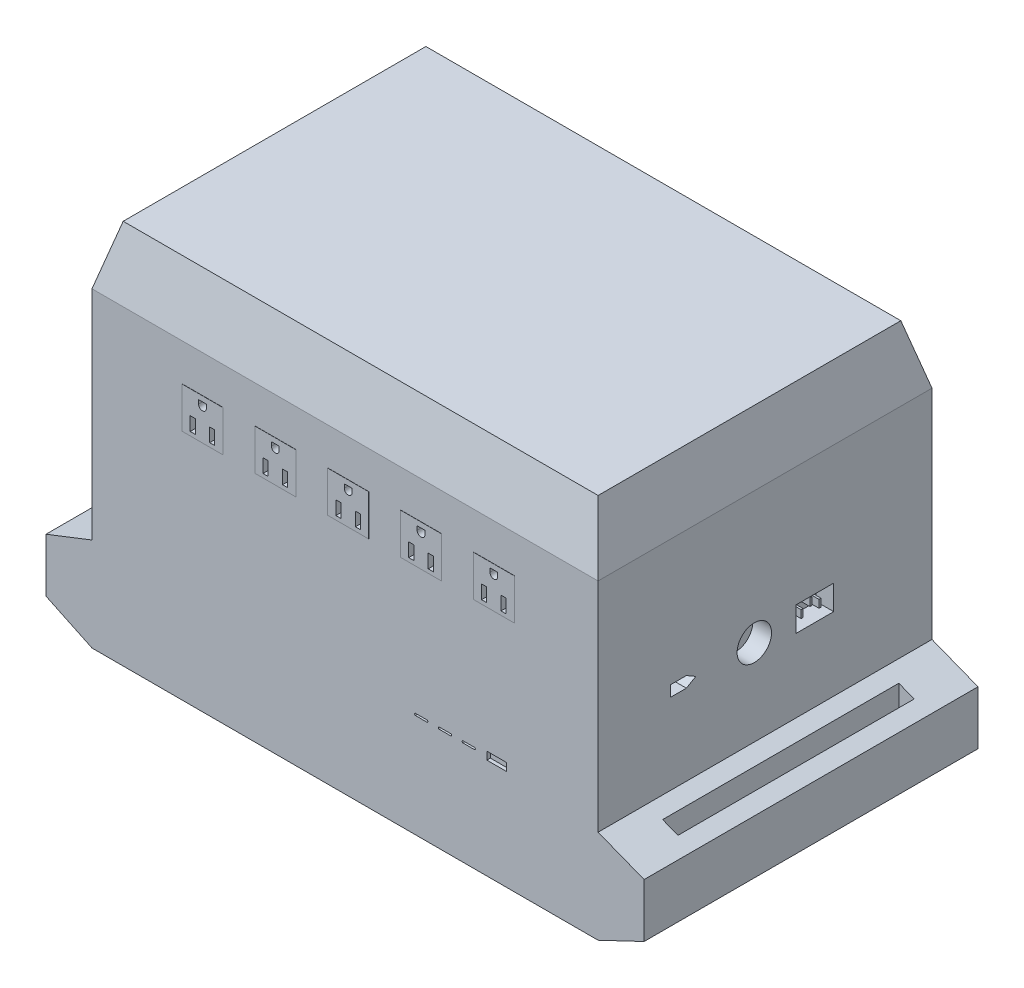
SolidWorks part; units mm, degrees
ref_plane "Front Plane" through (0, 0, 0) normal (0, 0, 1) x (1, 0, 0)
ref_plane "Top Plane" through (0, 0, 0) normal (0, 1, 0) x (1, 0, 0)
ref_plane "Right Plane" through (0, 0, 0) normal (1, 0, 0) x (0, 0, -1)
ref_plane "Plane17" through (153.035, 0, 0) normal (1, 0, 0) x (0, 0, -1)
sketch "Sketch222" plane through (153.035, 0, 0) normal (1, 0, 0) x (0, 0, -1)
  line L0 (0.0344, -137.6162) -> (-0.4201, -134.1674)
  line L1 (-0.4201, -134.1674) -> (-0.7623, -134.2123)
  line L2 (-0.7623, -134.2123) -> (-0.5399, -135.9027)
  line L3 (-0.5399, -135.9027) -> (-1.9253, -136.085)
  line L4 (-1.9253, -136.085) -> (-1.8804, -136.425)
  line L5 (-1.8804, -136.425) -> (-0.495, -136.2427)
  line L6 (-0.495, -136.2427) -> (-0.3527, -137.321)
  line L7 (-0.3527, -137.321) -> (-1.7381, -137.5033)
  line L8 (-1.7381, -137.5033) -> (-1.6932, -137.8434)
  line L9 (-1.6932, -137.8434) -> (0.0344, -137.6162)
extrude "Boss-Extrude62" add sketch "Sketch222" against normal blind 0.254 separate body
sketch "Sketch227" plane through (153.035, 0, 0) normal (1, 0, 0) x (0, 0, -1)
  line L0 (-2.6961, -138.3056) -> (-4.132, -136.7877)
  line L1 (-5.7965, -138.3617) -> (-4.3606, -139.8796)
  line L2 (-4.3606, -139.8796) -> (-4.1089, -139.6412)
  line L3 (-4.1089, -139.6412) -> (-5.5448, -138.1233)
  line L4 (-4.383, -137.0246) -> (-2.9471, -138.5426)
  line L5 (-2.9471, -138.5426) -> (-2.6961, -138.3056)
  arc A0 (-4.383, -137.0246) -> (-4.7111, -136.6979) centre (-7.9745, -140.3034) ccw
  ellipse E0 centre (-5.3112, -137.3021) end of major axis (-6.0324, -138.2441) minor radius 1.0176 (-4.6789, -136.3004) -> (-5.9914, -136.5388) ccw
  ellipse E1 centre (10.0574, -138.6279) end of major axis (26.4523, -140.0183) minor radius 3.9078 (-5.9914, -136.5388) -> (-5.7965, -138.3617) ccw
  ellipse E2 centre (-4.8312, -137.3712) end of major axis (-5.9904, -137.2348) minor radius 0.9225 (-5.7523, -136.7652) -> (-5.8918, -137.7061) ccw
  ellipse E3 centre (-5.3885, -137.8002) end of major axis (-4.9328, -136.5596) minor radius 0.909 (-4.7111, -136.6979) -> (-5.7523, -136.7652) ccw
  spline S0 degree 3 poles (-4.6789, -136.3004) (-4.6624, -136.3102) (-4.6266, -136.3315) (-4.5722, -136.3711) (-4.513, -136.4202) (-4.4466, -136.4758) (-4.376, -136.5418) (-4.2991, -136.6156) (-4.2171, -136.6987) (-4.1611, -136.7572) (-4.132, -136.7877) knots 0 0 0 0 0.078415 0.170067 0.274567 0.392386 0.523435 0.669246 0.827858 1 1 1 1
  spline S1 degree 3 poles (-5.8918, -137.7061) (-5.8855, -137.7172) (-5.8714, -137.7417) (-5.8438, -137.7795) (-5.8106, -137.8234) (-5.77, -137.8724) (-5.7243, -137.9282) (-5.6698, -137.9879) (-5.6096, -138.054) (-5.567, -138.0995) (-5.5448, -138.1233) knots 0 0 0 0 0.070557 0.155715 0.257861 0.374284 0.507047 0.65592 0.820233 1 1 1 1
extrude "Boss-Extrude63" add sketch "Sketch227" against normal blind 0.254 separate body
sketch "Sketch232" plane through (153.035, 0, 0) normal (1, 0, 0) x (0, 0, -1)
  line L0 (-5.9996, -142.3008) -> (-5.8474, -142.6247)
  line L1 (-7.6318, -140.5242) -> (-7.7447, -140.1967)
  arc A0 (-6.2751, -141.3262) -> (-6.7091, -141.6957) centre (-0.9141, -148.0627) ccw
  ellipse E0 centre (-7.9911, -141.4298) end of major axis (-8.3755, -140.6742) minor radius 0.6844 (-8.6849, -141.0759) -> (-7.969, -142.2384) ccw
  ellipse E1 centre (-5.8463, -141.6386) end of major axis (-5.9012, -141.2006) minor radius 0.4102 (-5.4506, -141.7644) -> (-5.7864, -141.2035) ccw
  ellipse E2 centre (-6.1816, -141.8844) end of major axis (-5.2666, -141.1179) minor radius 0.9529 (-5.0993, -141.8458) -> (-5.7261, -140.8481) ccw
  ellipse E3 centre (-7.0933, -141.4227) end of major axis (-7.5943, -141.8245) minor radius 0.0933 (-7.5364, -141.8226) -> (-6.8654, -141.3522) ccw
  ellipse E4 centre (-7.6202, -141.121) end of major axis (-7.0908, -140.4981) minor radius 0.6772 (-8.3455, -141.1138) -> (-7.8982, -141.8675) ccw
  spline S0 degree 3 poles (-8.6849, -141.0759) (-8.6789, -141.0504) (-8.6672, -140.9996) (-8.643, -140.9262) (-8.615, -140.8552) (-8.5813, -140.7877) (-8.5433, -140.7227) (-8.5004, -140.6608) (-8.4525, -140.6018) (-8.3997, -140.5454) (-8.3412, -140.4916) (-8.2757, -140.4414) (-8.2039, -140.3934) (-8.1249, -140.3488) (-8.0397, -140.3059) (-7.9471, -140.267) (-7.8486, -140.2296) (-7.7798, -140.2079) (-7.7447, -140.1967) knots 0 0 0 0 0.05791 0.114827 0.170369 0.226182 0.281195 0.336413 0.392147 0.448698 0.506734 0.567387 0.630606 0.69713 0.767471 0.840942 0.918622 1 1 1 1
  spline S1 degree 3 poles (-6.7091, -141.6957) (-6.7433, -141.7258) (-6.8095, -141.7842) (-6.9085, -141.8657) (-7.0037, -141.9387) (-7.095, -142.0033) (-7.1817, -142.0603) (-7.2645, -142.109) (-7.3434, -142.1492) (-7.4188, -142.182) (-7.4919, -142.2071) (-7.5629, -142.228) (-7.633, -142.2424) (-7.7023, -142.2527) (-7.7705, -142.2567) (-7.8378, -142.256) (-7.904, -142.2508) (-7.9473, -142.2425) (-7.969, -142.2384) knots 0 0 0 0 0.095916 0.185763 0.270011 0.34838 0.421264 0.488528 0.550368 0.607681 0.661372 0.71308 0.763362 0.812076 0.86039 0.907141 0.953564 1 1 1 1
  spline S2 degree 3 poles (-5.7864, -141.2035) (-5.8051, -141.2004) (-5.8422, -141.194) (-5.8989, -141.1912) (-5.9557, -141.195) (-6.0139, -141.2041) (-6.0742, -141.2212) (-6.1376, -141.2482) (-6.2061, -141.2822) (-6.2513, -141.3111) (-6.2751, -141.3262) knots 0 0 0 0 0.109431 0.217787 0.327569 0.438545 0.558024 0.68966 0.836669 1 1 1 1
  spline S3 degree 3 poles (-5.9996, -142.3008) (-5.9759, -142.2895) (-5.9302, -142.2676) (-5.865, -142.2338) (-5.805, -142.2012) (-5.7516, -142.1681) (-5.7032, -142.137) (-5.6621, -142.1048) (-5.625, -142.0754) (-5.5854, -142.0349) (-5.5424, -141.9833) (-5.5017, -141.9153) (-5.47, -141.8422) (-5.4571, -141.7906) (-5.4506, -141.7644) knots 0 0 0 0 0.098352 0.190043 0.275139 0.354175 0.425614 0.490624 0.549741 0.603019 0.702635 0.800901 0.89903 1 1 1 1
  spline S4 degree 3 poles (-5.0993, -141.8458) (-5.1091, -141.8851) (-5.1284, -141.9633) (-5.1753, -142.0749) (-5.2372, -142.1786) (-5.2996, -142.2594) (-5.3587, -142.3199) (-5.4092, -142.3657) (-5.4668, -142.41) (-5.5302, -142.4547) (-5.6006, -142.4977) (-5.6769, -142.5413) (-5.7597, -142.5841) (-5.8176, -142.6109) (-5.8474, -142.6247) knots 0 0 0 0 0.107801 0.214363 0.320668 0.42885 0.485185 0.545551 0.610286 0.678655 0.751879 0.829919 0.912587 1 1 1 1
  spline S5 degree 3 poles (-6.2863, -140.9189) (-6.2631, -140.9087) (-6.2172, -140.8887) (-6.1472, -140.8649) (-6.077, -140.8472) (-6.007, -140.8351) (-5.9366, -140.8296) (-5.8663, -140.8297) (-5.7958, -140.8349) (-5.7494, -140.8437) (-5.7261, -140.8481) knots 0 0 0 0 0.132319 0.261173 0.385741 0.509487 0.631872 0.753868 0.876254 1 1 1 1
  spline S6 degree 3 poles (-6.8654, -141.3522) (-6.8324, -141.3236) (-6.7692, -141.2689) (-6.6774, -141.1926) (-6.5936, -141.1249) (-6.5178, -141.0658) (-6.4485, -141.0169) (-6.3883, -140.9753) (-6.3353, -140.9429) (-6.3016, -140.9264) (-6.2863, -140.9189) knots 0 0 0 0 0.181047 0.345853 0.493713 0.626794 0.743261 0.844919 0.929503 1 1 1 1
  spline S7 degree 3 poles (-7.8982, -141.8675) (-7.8693, -141.872) (-7.8107, -141.881) (-7.7201, -141.8768) (-7.6275, -141.8574) (-7.5675, -141.8345) (-7.5364, -141.8226) knots 0 0 0 0 0.236659 0.47937 0.730941 1 1 1 1
  spline S8 degree 3 poles (-7.6318, -140.5242) (-7.6816, -140.5402) (-7.777, -140.5709) (-7.9096, -140.6277) (-8.0253, -140.6911) (-8.1242, -140.7614) (-8.2062, -140.839) (-8.2707, -140.924) (-8.3197, -141.0154) (-8.3369, -141.0811) (-8.3455, -141.1138) knots 0 0 0 0 0.161453 0.30907 0.444319 0.567798 0.682555 0.791157 0.895979 1 1 1 1
extrude "Boss-Extrude64" add sketch "Sketch232" against normal blind 0.254 separate body
sketch "Sketch237" plane through (153.035, 0, 0) normal (1, 0, 0) x (0, 0, -1)
  line L0 (-5.2735, -144.1601) -> (-8.4966, -145.4361)
  line L1 (-8.4966, -145.4361) -> (-7.7702, -147.2696)
  line L2 (-7.7702, -147.2696) -> (-7.4526, -147.1441)
  line L3 (-7.4526, -147.1441) -> (-8.0514, -145.6324)
  line L4 (-8.0514, -145.6324) -> (-6.7872, -145.1318)
  line L5 (-6.7872, -145.1318) -> (-6.1885, -146.6435)
  line L6 (-6.1885, -146.6435) -> (-5.873, -146.518)
  line L7 (-5.873, -146.518) -> (-6.4717, -145.0063)
  line L8 (-6.4717, -145.0063) -> (-5.4635, -144.6074)
  line L9 (-5.4635, -144.6074) -> (-4.8598, -146.1323)
  line L10 (-4.8598, -146.1323) -> (-4.5422, -146.0068)
  line L11 (-4.5422, -146.0068) -> (-5.2735, -144.1601)
extrude "Boss-Extrude65" add sketch "Sketch237" against normal blind 0.254 separate body
ref_plane "Plane18" through (0, 0, -101.854) normal (0, 0, -1) x (-1, 0, 0)
sketch "Sketch242" plane through (0, 0, -101.854) normal (0, 0, -1) x (-1, 0, 0)
  line L0 (167.1498, -19.1227) -> (-162.8502, -19.1227)
  line L1 (-162.8502, -19.1227) -> (-162.8502, -199.1227)
  line L2 (-162.8502, -199.1227) -> (-192.8502, -210.8394)
  line L3 (-192.8502, -210.8394) -> (-192.8502, -245.8394)
  line L4 (-192.8502, -245.8394) -> (-162.8502, -260.1227)
  line L5 (-162.8502, -260.1227) -> (167.1498, -260.1227)
  line L6 (167.1498, -260.1227) -> (197.1498, -245.8394)
  line L7 (197.1498, -245.8394) -> (197.1498, -210.8394)
  line L8 (197.1498, -210.8394) -> (167.1498, -199.1227)
  line L9 (167.1498, -199.1227) -> (167.1498, -19.1227)
  dimension "D1" = 241
  dimension "D2" = 330
  dimension "D3" = 180
  dimension "D4" = 35
  dimension "D5" = 390
  dimension "D6" = 32.2069
  dimension "D7" = 33.2267
  dimension "D8" = 30
  dimension "D9" = 14.2832
extrude "Boss-Extrude66" add sketch "Sketch242" against normal blind 17.62 and the other way blind 14 separate body
sketch "Sketch243" plane through (0, 0, -84.234) normal (0, 0, 1) x (1, 0, 0)
  line L0 (182.8502, -250.6005) -> (172.8502, -255.3616)
  line L1 (172.8502, -255.3616) -> (172.8502, -203.0282)
  line L2 (172.8502, -203.0282) -> (182.8502, -206.9338)
  line L3 (182.8502, -206.9338) -> (182.8502, -250.6005)
  line L4 (162.8502, -199.1227) -> (192.8502, -210.8394) construction
  line L5 (192.8502, -245.8394) -> (162.8502, -260.1227) construction
  line L6 (192.8502, -210.8394) -> (192.8502, -245.8394) construction
  line L7 (162.8502, -19.1227) -> (162.8502, -199.1227) construction
  dimension "D1" = 10
  dimension "D2" = 10
sketch "Sketch244" plane through (0, 0, -84.234) normal (0, 0, 1) x (1, 0, 0)
  line L0 (-167.1498, -260.1227) -> (-197.1498, -245.8394)
  line L1 (-197.1498, -245.8394) -> (-197.1498, -210.8394)
  line L2 (-197.1498, -210.8394) -> (-167.1498, -199.1227)
  line L3 (-167.1498, -199.1227) -> (-167.1498, -19.1227)
  line L4 (-167.1498, -19.1227) -> (162.8502, -19.1227)
  line L5 (162.8502, -19.1227) -> (162.8502, -199.1227)
  line L6 (162.8502, -199.1227) -> (192.8502, -210.8394)
  line L7 (192.8502, -210.8394) -> (192.8502, -245.8394)
  line L8 (192.8502, -245.8394) -> (162.8502, -260.1227)
  line L9 (162.8502, -260.1227) -> (-167.1498, -260.1227)
  line L10 (-167.1498, -199.1227) -> (-167.1498, -19.1227) construction
  line L11 (-167.1498, -19.1227) -> (162.8502, -19.1227) construction
  line L12 (162.8502, -19.1227) -> (162.8502, -199.1227) construction
  line L13 (192.8502, -210.8394) -> (192.8502, -245.8394) construction
  line L14 (162.8502, -199.1227) -> (192.8502, -210.8394) construction
  line L15 (192.8502, -245.8394) -> (162.8502, -260.1227) construction
  line L16 (162.8502, -260.1227) -> (-167.1498, -260.1227) construction
  line L17 (-167.1498, -260.1227) -> (-197.1498, -245.8394) construction
  line L18 (-197.1498, -245.8394) -> (-197.1498, -210.8394) construction
  line L19 (-197.1498, -210.8394) -> (-167.1498, -199.1227) construction
  line L20 (-197.1498, -245.8394) -> (-197.1498, -210.8394) construction
  line L21 (-197.1498, -210.8394) -> (-167.1498, -199.1227) construction
extrude "Boss-Extrude68" add sketch "Sketch244" along normal blind 168.468
sketch "Sketch246" plane through (0, 0, 84.234) normal (0, 0, 1) x (1, 0, 0)
  line L0 (162.8502, -199.1227) -> (192.8502, -210.8394)
  line L1 (192.8502, -210.8394) -> (192.8502, -245.8394)
  line L2 (192.8502, -245.8394) -> (162.8502, -260.1227)
  line L3 (162.8502, -260.1227) -> (-167.1498, -260.1227)
  line L4 (-167.1498, -260.1227) -> (-197.1498, -245.8394)
  line L5 (-197.1498, -245.8394) -> (-197.1498, -210.8394)
  line L6 (-197.1498, -210.8394) -> (-167.1498, -199.1227)
  line L7 (-167.1498, -199.1227) -> (-167.1498, -19.1227)
  line L8 (-167.1498, -19.1227) -> (162.8502, -19.1227)
  line L9 (162.8502, -19.1227) -> (162.8502, -199.1227)
  line L10 (162.8502, -19.1227) -> (-167.1498, -19.1227) construction
  line L11 (-167.1498, -19.1227) -> (-167.1498, -199.1227) construction
  line L12 (-197.1498, -210.8394) -> (-167.1498, -199.1227) construction
  line L13 (-197.1498, -245.8394) -> (-197.1498, -210.8394) construction
  line L14 (-167.1498, -260.1227) -> (-197.1498, -245.8394) construction
  line L15 (162.8502, -260.1227) -> (-167.1498, -260.1227) construction
  line L16 (192.8502, -245.8394) -> (162.8502, -260.1227) construction
  line L17 (192.8502, -210.8394) -> (192.8502, -245.8394) construction
  line L18 (162.8502, -199.1227) -> (192.8502, -210.8394) construction
extrude "Boss-Extrude70" add sketch "Sketch246" along normal blind 17.62
ref_plane "Plane19" through (-163.703, 0, 0) normal (-1, 0, 0) x (0, 0, 1)
sketch "Sketch252" plane through (-163.703, 0, 0) normal (-1, 0, 0) x (0, 0, 1)
  line L0 (-11.7788, -143.2) -> (-12.4793, -143.2)
  line L1 (-13.9776, -142.264) -> (-14.0224, -143.6885)
  line L2 (-14.0224, -143.6885) -> (-14.0224, -139.7)
  line L3 (-14.0224, -139.7) -> (-13.634, -139.7)
  line L4 (-13.634, -139.7) -> (-13.634, -141.3154)
  line L5 (-13.634, -141.3154) -> (-12.0929, -141.3154)
  line L6 (-12.0929, -141.3154) -> (-12.0929, -139.7)
  line L7 (-12.0929, -139.7) -> (-11.7788, -139.7)
  line L8 (-11.7788, -139.7) -> (-11.7788, -143.2)
  arc A0 (-12.4793, -143.2) -> (-13.2722, -143.1523) centre (-12.5951, -138.5088) cw
  ellipse E0 centre (-12.9672, -142.209) end of major axis (-12.0813, -141.6743) minor radius 0.9414 (-13.9776, -142.264) -> (-13.2722, -143.1523) ccw
extrude "Boss-Extrude71" add sketch "Sketch252" along normal blind 0.254
chamfer "Chamfer7" distance 10.16 angle 75.069 4 edges at (-2.1498, -19.1227, -115.854) (162.8502, -19.1227, -7) (-167.1498, -19.1227, -7) (-2.1498, -19.1227, 101.854)
sketch "Sketch253" plane through (-167.1498, 0, 0) normal (-1, 0, 0) x (0, 0, 1)
  ellipse E0 centre (-2.0861, -141.2724) end of major axis (-3.3261, -139.6136) minor radius 1.9176 (-1.9295, -143.2897) -> (-0.1122, -141.4346) ccw
  ellipse E1 centre (-2.1642, -141.6778) end of major axis (-0.9066, -142.8229) minor radius 1.5373 (-3.7917, -141.4514) -> (-1.9295, -143.2897) ccw
  ellipse E2 centre (-2.2917, -141.1164) end of major axis (-1.1535, -139.9506) minor radius 1.3696 (-1.9575, -139.6103) -> (-3.7917, -141.4514) ccw
  ellipse E3 centre (-1.5964, -141.0847) end of major axis (-0.4364, -142.2065) minor radius 1.3366 (-0.1122, -141.4346) -> (-1.9575, -139.6103) ccw
extrude "Boss-Extrude72" add sketch "Sketch253" along normal blind 0.254
sketch "Sketch254" plane through (-167.4038, 0, 0) normal (-1, 0, 0) x (0, 0, 1)
  ellipse E0 centre (-1.6109, -141.7451) end of major axis (-3.1952, -140.5735) minor radius 1.6602 (-1.9449, -139.9692) -> (-3.4776, -141.4521) ccw
  ellipse E1 centre (-1.8216, -141.3893) end of major axis (-3.4031, -141.9274) minor radius 1.5262 (-3.4776, -141.4521) -> (-1.9449, -142.9308) ccw
  ellipse E2 centre (-2.0851, -141.3466) end of major axis (-0.588, -142.1202) minor radius 1.5565 (-1.9449, -142.9308) -> (-0.4263, -141.436) ccw
  ellipse E3 centre (-1.6563, -141.149) end of major axis (-2.6855, -140.3274) minor radius 1.086 (-0.4263, -141.436) -> (-1.9449, -139.9692) ccw
extrude "Cut-Extrude49" cut sketch "Sketch254" against normal blind 0.254 from surface at -0.254 starting at face at (-167.1498, -141.4495, -1.9512)
sketch "Sketch256" plane through (-167.1498, 0, 0) normal (-1, 0, 0) x (0, 0, 1)
  line L0 (11.2404, -142.1231) -> (11.5545, -142.1231)
  line L1 (10.0632, -140.9929) -> (10.9389, -140.059)
  line L2 (10.9389, -140.059) -> (9.3109, -140.059)
  line L3 (9.3109, -140.059) -> (9.3109, -139.7)
  line L4 (9.3109, -139.7) -> (11.6891, -139.7)
  line L5 (11.6891, -139.7) -> (11.6891, -139.7318)
  ellipse E0 centre (10.5178, -142.2084) end of major axis (11.0326, -141.237) minor radius 1.0186 (10.4131, -143.2897) -> (11.5545, -142.1231) ccw
  ellipse E1 centre (10.2761, -142.3526) end of major axis (9.6685, -141.5951) minor radius 0.8865 (9.3558, -142.2493) -> (10.4131, -143.2897) ccw
  ellipse E2 centre (10.2745, -142.3612) end of major axis (9.7564, -141.9751) minor radius 0.5239 (9.6699, -142.2212) -> (10.4292, -142.9308) ccw
  ellipse E3 centre (10.1862, -141.7824) end of major axis (9.4711, -140.775) minor radius 0.9527 (10.4292, -142.9308) -> (11.2404, -142.1231) ccw
  spline S0 degree 3 poles (9.3558, -142.2493) (9.3575, -142.2005) (9.3608, -142.1039) (9.3895, -141.9619) (9.4345, -141.8244) (9.488, -141.7134) (9.5418, -141.6238) (9.5915, -141.5508) (9.6489, -141.4717) (9.7149, -141.3866) (9.7904, -141.2967) (9.8726, -141.1995) (9.9651, -141.0981) (10.0297, -141.0288) (10.0632, -140.9929) knots 0 0 0 0 0.098685 0.195638 0.292371 0.391069 0.444585 0.503948 0.57006 0.642614 0.721977 0.807955 0.900487 1 1 1 1
  spline S1 degree 3 poles (11.6891, -139.7318) (11.2366, -140.204) (10.7511, -140.7108) (10.2352, -141.2493) (10.1454, -141.346) (10.0647, -141.4357) (9.9929, -141.5187) (9.93, -141.5945) (9.8762, -141.6637) (9.8313, -141.7257) (9.7837, -141.7986) (9.7383, -141.8877) (9.6984, -141.996) (9.6742, -142.1078) (9.6713, -142.1833) (9.6699, -142.2212) knots -1.516771 -1.516771 -1.516771 -1.516771 0 0.110794 0.212813 0.306078 0.390617 0.467233 0.534451 0.593867 0.644833 0.736221 0.825037 0.911992 1 1 1 1
extrude "Boss-Extrude73" add sketch "Sketch256" along normal blind 0.254
sketch "Sketch257" plane through (-167.1498, 0, 0) normal (-1, 0, 0) x (0, 0, 1)
  line L0 (-4.2853, -143.2) -> (-4.6092, -143.2)
  line L1 (-4.6092, -143.2) -> (-5.2949, -140.6311)
  line L2 (-5.2949, -140.6311) -> (-6.3358, -143.2578)
  line L3 (-6.3358, -143.2578) -> (-7.359, -140.6507)
  line L4 (-7.359, -140.6507) -> (-8.0475, -143.2)
  line L5 (-8.0475, -143.2) -> (-8.3686, -143.2)
  line L6 (-8.3686, -143.2) -> (-8.3686, -139.7)
  line L7 (-8.3686, -139.7) -> (-7.38, -139.7)
  line L8 (-7.38, -139.7) -> (-6.3269, -142.3755)
  line L9 (-6.3269, -142.3755) -> (-5.2626, -139.7)
  line L10 (-5.2626, -139.7) -> (-4.2853, -139.7)
  line L11 (-4.2853, -139.7) -> (-4.2853, -143.2)
extrude "Boss-Extrude74" add sketch "Sketch257" along normal blind 0.254
sketch "Sketch258" plane through (-167.1498, 0, 0) normal (-1, 0, 0) x (0, 0, 1)
  line L0 (-9.1763, -143.2) -> (-11.1506, -143.2)
  line L1 (-11.1506, -143.2) -> (-11.1506, -142.841)
  line L2 (-11.1506, -142.841) -> (-9.4904, -142.841)
  line L3 (-9.4904, -142.841) -> (-9.4904, -141.7641)
  line L4 (-9.4904, -141.7641) -> (-11.1506, -141.7641)
  line L5 (-11.1506, -141.7641) -> (-11.1506, -141.4051)
  line L6 (-11.1506, -141.4051) -> (-9.4904, -141.4051)
  line L7 (-9.4904, -141.4051) -> (-9.4904, -140.059)
  line L8 (-9.4904, -140.059) -> (-11.1506, -140.059)
  line L9 (-11.1506, -140.059) -> (-11.1506, -139.7)
  line L10 (-11.1506, -139.7) -> (-9.1763, -139.7)
  line L11 (-9.1763, -139.7) -> (-9.1763, -143.2)
extrude "Boss-Extrude75" add sketch "Sketch258" along normal blind 0.254
sketch "Sketch265" plane through (-163.703, 0, 0) normal (-1, 0, 0) x (0, 0, 1)
  line L0 (13.6375, -143.2) -> (12.9904, -143.2)
  line L1 (12.9904, -143.2) -> (12.9904, -139.7)
  line L2 (12.9904, -139.7) -> (13.3045, -139.7)
  line L3 (13.3045, -139.7) -> (13.3045, -142.841)
  line L4 (13.3045, -142.841) -> (13.6375, -142.841)
  line L5 (13.6375, -142.841) -> (13.6375, -143.2)
extrude "Boss-Extrude76" add sketch "Sketch265" along normal blind 0.254
sketch "Sketch272" plane through (-163.703, 0, 0) normal (-1, 0, 0) x (0, 0, 1)
  line L0 (7.6058, -143.2) -> (7.2692, -143.2)
  line L1 (7.2692, -143.2) -> (6.1033, -140.4439)
  line L2 (6.1033, -140.4439) -> (4.9366, -143.2)
  line L3 (4.9366, -143.2) -> (4.5994, -143.2)
  line L4 (4.5994, -143.2) -> (4.5994, -136.0939)
  line L5 (4.5994, -136.0939) -> (7.6058, -143.2)
extrude "Boss-Extrude77" add sketch "Sketch272" along normal blind 0.254
ref_plane "Plane20" through (0, 0, 101.854) normal (0, 0, 1) x (1, 0, 0)
sketch "Sketch279" plane through (0, 0, 101.854) normal (0, 0, 1) x (1, 0, 0)
  line L0 (90.297, -194.691) -> (102.997, -194.691)
  line L1 (102.997, -194.691) -> (102.997, -189.611)
  line L2 (102.997, -189.611) -> (90.297, -189.611)
  line L3 (90.297, -189.611) -> (90.297, -194.691)
extrude "Cut-Extrude51" cut sketch "Sketch279" against normal blind 12.7
sketch "Sketch280" plane through (0, 0, 89.154) normal (0, 0, 1) x (1, 0, 0)
  line L0 (91.313, -193.675) -> (91.313, -190.627)
  line L1 (91.313, -190.627) -> (101.981, -190.627)
  line L2 (101.981, -190.627) -> (101.981, -193.675)
  line L3 (101.981, -193.675) -> (91.313, -193.675)
extrude "Boss-Extrude78" add sketch "Sketch280" along normal blind 11.43
sketch "Sketch281" plane through (0, 0, 101.854) normal (0, 0, 1) x (1, 0, 0)
  line L0 (82.169, -191.516) -> (74.803, -191.516)
  line L1 (74.803, -192.786) -> (82.169, -192.786)
  arc A0 (74.803, -191.516) -> (74.803, -192.786) centre (74.803, -192.151) ccw
  arc A1 (82.169, -192.786) -> (82.169, -191.516) centre (82.169, -192.151) ccw
extrude "Cut-Extrude52" cut sketch "Sketch281" against normal blind 12.7
sketch "Sketch282" plane through (0, 0, 89.154) normal (0, 0, 1) x (1, 0, 0)
  line L0 (74.803, -192.024) -> (82.169, -192.024)
  line L1 (82.169, -192.278) -> (74.803, -192.278)
  arc A0 (82.169, -192.024) -> (82.169, -192.278) centre (82.169, -192.151) cw
  arc A1 (74.803, -192.278) -> (74.803, -192.024) centre (74.803, -192.151) cw
extrude "Boss-Extrude79" add sketch "Sketch282" along normal blind 11.43
sketch "Sketch290" plane through (0, 0, 101.854) normal (0, 0, 1) x (1, 0, 0)
  line L0 (59.309, -192.786) -> (66.675, -192.786)
  line L1 (66.675, -191.516) -> (59.309, -191.516)
  arc A0 (66.675, -192.786) -> (66.675, -191.516) centre (66.675, -192.151) ccw
  arc A1 (59.309, -191.516) -> (59.309, -192.786) centre (59.309, -192.151) ccw
extrude "Cut-Extrude53" cut sketch "Sketch290" against normal blind 12.7
sketch "Sketch291" plane through (0, 0, 89.154) normal (0, 0, 1) x (1, 0, 0)
  line L0 (66.675, -192.278) -> (59.309, -192.278)
  line L1 (59.309, -192.024) -> (66.675, -192.024)
  arc A0 (59.309, -192.278) -> (59.309, -192.024) centre (59.309, -192.151) cw
  arc A1 (66.675, -192.024) -> (66.675, -192.278) centre (66.675, -192.151) cw
extrude "Boss-Extrude80" add sketch "Sketch291" along normal blind 11.43
sketch "Sketch292" plane through (0, 0, 101.854) normal (0, 0, 1) x (1, 0, 0)
  line L0 (43.815, -192.786) -> (51.181, -192.786)
  line L1 (51.181, -191.516) -> (43.815, -191.516)
  arc A0 (51.181, -192.786) -> (51.181, -191.516) centre (51.181, -192.151) ccw
  arc A1 (43.815, -191.516) -> (43.815, -192.786) centre (43.815, -192.151) ccw
extrude "Cut-Extrude54" cut sketch "Sketch292" against normal blind 12.7
sketch "Sketch293" plane through (0, 0, 89.154) normal (0, 0, 1) x (1, 0, 0)
  line L0 (51.181, -192.278) -> (43.815, -192.278)
  line L1 (43.815, -192.024) -> (51.181, -192.024)
  arc A0 (43.815, -192.278) -> (43.815, -192.024) centre (43.815, -192.151) cw
  arc A1 (51.181, -192.024) -> (51.181, -192.278) centre (51.181, -192.151) cw
extrude "Boss-Extrude81" add sketch "Sketch293" along normal blind 11.43
ref_plane "Plane21" through (163.703, 0, 0) normal (1, 0, 0) x (0, 0, -1)
sketch "Sketch301" plane through (163.703, 0, 0) normal (1, 0, 0) x (0, 0, -1)
  line L0 (51.7652, -135.255) -> (27.2288, -135.255)
  line L1 (27.2288, -135.255) -> (27.2288, -151.384)
  line L2 (27.2288, -151.384) -> (51.7652, -151.384)
  line L3 (51.7652, -151.384) -> (51.7652, -135.255)
extrude "Cut-Extrude55" cut sketch "Sketch301" against normal blind 11.43 from surface at -0.8528 starting at face at (162.8502, -128.1727, -7)
sketch "Sketch302" plane through (151.4202, 0, 0) normal (1, 0, 0) x (0, 0, -1)
  line L0 (40.132, -143.3367) -> (38.862, -143.3367)
  line L1 (38.862, -143.3367) -> (38.862, -138.2567)
  line L2 (38.862, -138.2567) -> (40.132, -138.2567)
  line L3 (40.132, -138.2567) -> (40.132, -143.3367)
extrude "Boss-Extrude82" add sketch "Sketch302" along normal blind 8.89
sketch "Sketch303" plane through (151.4202, 0, 0) normal (1, 0, 0) x (0, 0, -1)
  line L0 (34.3011, -147.2296) -> (33.0311, -147.2296)
  line L1 (33.0311, -147.2296) -> (33.0311, -142.1496)
  line L2 (33.0311, -142.1496) -> (34.3011, -142.1496)
  line L3 (34.3011, -142.1496) -> (34.3011, -147.2296)
extrude "Boss-Extrude83" add sketch "Sketch303" along normal blind 8.89
sketch "Sketch304" plane through (151.4202, 0, 0) normal (1, 0, 0) x (0, 0, -1)
  line L0 (45.9629, -147.2296) -> (44.6929, -147.2296)
  line L1 (44.6929, -147.2296) -> (44.6929, -142.1496)
  line L2 (44.6929, -142.1496) -> (45.9629, -142.1496)
  line L3 (45.9629, -142.1496) -> (45.9629, -147.2296)
extrude "Boss-Extrude84" add sketch "Sketch304" along normal blind 8.89
sketch "Sketch305" plane through (162.8502, 0, 0) normal (1, 0, 0) x (0, 0, -1)
  line L0 (-44.2985, -146.558) -> (-38.1393, -143.002)
  line L1 (-38.1393, -143.002) -> (-44.2985, -139.446)
  line L2 (-44.2985, -139.446) -> (-54.61, -139.446)
  line L3 (-54.61, -139.446) -> (-54.61, -146.558)
  line L4 (-54.61, -146.558) -> (-44.2985, -146.558)
extrude "Cut-Extrude56" cut sketch "Sketch305" against normal blind 12.7 from surface at 0 starting at face at (162.8502, -128.1727, -7)
sketch "Sketch312" plane through (-163.703, 0, 0) normal (-1, 0, 0) x (0, 0, 1)
  line L0 (2.5801, -143.2) -> (1.8937, -143.2)
  line L1 (2.0157, -141.3154) -> (2.266, -141.3154)
  line L2 (2.266, -141.3154) -> (2.266, -139.7)
  line L3 (2.266, -139.7) -> (2.5801, -139.7)
  line L4 (2.5801, -139.7) -> (2.5801, -143.2)
  ellipse E0 centre (1.8791, -143.1329) end of major axis (2.6804, -143.1327) minor radius 0.0672 (1.0966, -143.1474) -> (1.8937, -143.2) ccw
  ellipse E1 centre (1.9044, -141.8509) end of major axis (3.2154, -140.8846) minor radius 1.1514 (0.4263, -142.2612) -> (1.0966, -143.1474) ccw
  ellipse E2 centre (1.9849, -142.7491) end of major axis (3.3715, -143.7998) minor radius 1.1791 (1.1246, -141.3729) -> (0.4263, -142.2612) ccw
  ellipse E3 centre (1.6823, -141.3543) end of major axis (2.2401, -141.3352) minor radius 0.0343 (2.0157, -141.3154) -> (1.1246, -141.3729) ccw
extrude "Boss-Extrude85" add sketch "Sketch312" along normal blind 0.254
sketch "Sketch321" plane through (0, 0, 101.854) normal (0, 0, 1) x (1, 0, 0)
  line L0 (-13.335, -81.534) -> (13.335, -81.534)
  line L1 (13.335, -81.534) -> (13.335, -108.204)
  line L2 (13.335, -108.204) -> (-13.335, -108.204)
  line L3 (-13.335, -108.204) -> (-13.335, -81.534)
extrude "Boss-Extrude86" add sketch "Sketch321" along normal blind 0.127
sketch "Sketch322" plane through (0, 0, 101.981) normal (0, 0, 1) x (1, 0, 0)
  line L0 (2.54, -84.963) -> (-2.54, -84.963)
  line L1 (-2.54, -84.963) -> (-2.54, -87.503)
  line L2 (2.54, -87.503) -> (2.54, -84.963)
  arc A0 (-2.54, -87.503) -> (2.54, -87.503) centre (0, -87.503) ccw
extrude "Cut-Extrude58" cut sketch "Sketch322" against normal blind 5.08
sketch "Sketch323" plane through (0, 0, 101.981) normal (0, 0, 1) x (1, 0, 0)
  line L0 (-8.001, -105.664) -> (-4.699, -105.664)
  line L1 (-4.699, -105.664) -> (-4.699, -96.774)
  line L2 (-4.699, -96.774) -> (-8.001, -96.774)
  line L3 (-8.001, -96.774) -> (-8.001, -105.664)
extrude "Cut-Extrude59" cut sketch "Sketch323" against normal blind 5.08
ref_plane "Plane22" through (0, 0, 101.981) normal (0, 0, 1) x (1, 0, 0)
sketch "Sketch332" plane through (0, 0, 101.981) normal (0, 0, 1) x (1, 0, 0)
  line L0 (4.699, -105.664) -> (8.001, -105.664)
  line L1 (8.001, -105.664) -> (8.001, -96.774)
  line L2 (8.001, -96.774) -> (4.699, -96.774)
  line L3 (4.699, -96.774) -> (4.699, -105.664)
extrude "Cut-Extrude60" cut sketch "Sketch332" against normal blind 5.08
sketch "Sketch333" plane through (0, 0, 101.854) normal (0, 0, 1) x (1, 0, 0)
  line L0 (-60.833, -81.534) -> (-34.163, -81.534)
  line L1 (-34.163, -81.534) -> (-34.163, -108.204)
  line L2 (-34.163, -108.204) -> (-60.833, -108.204)
  line L3 (-60.833, -108.204) -> (-60.833, -81.534)
extrude "Boss-Extrude87" add sketch "Sketch333" along normal blind 0.127
sketch "Sketch334" plane through (0, 0, 101.981) normal (0, 0, 1) x (1, 0, 0)
  line L0 (-55.499, -105.664) -> (-52.197, -105.664)
  line L1 (-52.197, -105.664) -> (-52.197, -96.774)
  line L2 (-52.197, -96.774) -> (-55.499, -96.774)
  line L3 (-55.499, -96.774) -> (-55.499, -105.664)
extrude "Cut-Extrude61" cut sketch "Sketch334" against normal blind 5.08
sketch "Sketch335" plane through (0, 0, 101.981) normal (0, 0, 1) x (1, 0, 0)
  line L0 (-44.958, -84.963) -> (-50.038, -84.963)
  line L1 (-50.038, -84.963) -> (-50.038, -87.503)
  line L2 (-44.958, -87.503) -> (-44.958, -84.963)
  arc A0 (-50.038, -87.503) -> (-44.958, -87.503) centre (-47.498, -87.503) ccw
extrude "Cut-Extrude62" cut sketch "Sketch335" against normal blind 5.08
sketch "Sketch336" plane through (0, 0, 101.981) normal (0, 0, 1) x (1, 0, 0)
  line L0 (-42.799, -105.664) -> (-39.497, -105.664)
  line L1 (-39.497, -105.664) -> (-39.497, -96.774)
  line L2 (-39.497, -96.774) -> (-42.799, -96.774)
  line L3 (-42.799, -96.774) -> (-42.799, -105.664)
extrude "Cut-Extrude63" cut sketch "Sketch336" against normal blind 5.08
sketch "Sketch337" plane through (0, 0, 101.854) normal (0, 0, 1) x (1, 0, 0)
  line L0 (-108.331, -81.534) -> (-81.661, -81.534)
  line L1 (-81.661, -81.534) -> (-81.661, -108.204)
  line L2 (-81.661, -108.204) -> (-108.331, -108.204)
  line L3 (-108.331, -108.204) -> (-108.331, -81.534)
extrude "Boss-Extrude88" add sketch "Sketch337" along normal blind 0.127
sketch "Sketch338" plane through (0, 0, 101.981) normal (0, 0, 1) x (1, 0, 0)
  line L0 (-90.297, -105.664) -> (-86.995, -105.664)
  line L1 (-86.995, -105.664) -> (-86.995, -96.774)
  line L2 (-86.995, -96.774) -> (-90.297, -96.774)
  line L3 (-90.297, -96.774) -> (-90.297, -105.664)
extrude "Cut-Extrude64" cut sketch "Sketch338" against normal blind 5.08
sketch "Sketch339" plane through (0, 0, 101.981) normal (0, 0, 1) x (1, 0, 0)
  line L0 (-102.997, -105.664) -> (-99.695, -105.664)
  line L1 (-99.695, -105.664) -> (-99.695, -96.774)
  line L2 (-99.695, -96.774) -> (-102.997, -96.774)
  line L3 (-102.997, -96.774) -> (-102.997, -105.664)
extrude "Cut-Extrude65" cut sketch "Sketch339" against normal blind 5.08
sketch "Sketch340" plane through (0, 0, 101.981) normal (0, 0, 1) x (1, 0, 0)
  line L0 (-92.456, -84.963) -> (-97.536, -84.963)
  line L1 (-97.536, -84.963) -> (-97.536, -87.503)
  line L2 (-92.456, -87.503) -> (-92.456, -84.963)
  arc A0 (-97.536, -87.503) -> (-92.456, -87.503) centre (-94.996, -87.503) ccw
extrude "Cut-Extrude66" cut sketch "Sketch340" against normal blind 5.08
sketch "Sketch341" plane through (0, 0, 101.854) normal (0, 0, 1) x (1, 0, 0)
  line L0 (34.163, -81.534) -> (60.833, -81.534)
  line L1 (60.833, -81.534) -> (60.833, -108.204)
  line L2 (60.833, -108.204) -> (34.163, -108.204)
  line L3 (34.163, -108.204) -> (34.163, -81.534)
extrude "Boss-Extrude89" add sketch "Sketch341" along normal blind 0.127
sketch "Sketch342" plane through (0, 0, 101.981) normal (0, 0, 1) x (1, 0, 0)
  line L0 (52.197, -105.664) -> (55.499, -105.664)
  line L1 (55.499, -105.664) -> (55.499, -96.774)
  line L2 (55.499, -96.774) -> (52.197, -96.774)
  line L3 (52.197, -96.774) -> (52.197, -105.664)
extrude "Cut-Extrude67" cut sketch "Sketch342" against normal blind 5.08
sketch "Sketch343" plane through (0, 0, 101.981) normal (0, 0, 1) x (1, 0, 0)
  line L0 (50.038, -84.963) -> (44.958, -84.963)
  line L1 (44.958, -84.963) -> (44.958, -87.503)
  line L2 (50.038, -87.503) -> (50.038, -84.963)
  arc A0 (44.958, -87.503) -> (50.038, -87.503) centre (47.498, -87.503) ccw
extrude "Cut-Extrude68" cut sketch "Sketch343" against normal blind 5.08
sketch "Sketch344" plane through (0, 0, 101.981) normal (0, 0, 1) x (1, 0, 0)
  line L0 (39.497, -105.664) -> (42.799, -105.664)
  line L1 (42.799, -105.664) -> (42.799, -96.774)
  line L2 (42.799, -96.774) -> (39.497, -96.774)
  line L3 (39.497, -96.774) -> (39.497, -105.664)
extrude "Cut-Extrude69" cut sketch "Sketch344" against normal blind 5.08
sketch "Sketch345" plane through (0, 0, 101.854) normal (0, 0, 1) x (1, 0, 0)
  line L0 (81.661, -81.534) -> (108.331, -81.534)
  line L1 (108.331, -81.534) -> (108.331, -108.204)
  line L2 (108.331, -108.204) -> (81.661, -108.204)
  line L3 (81.661, -108.204) -> (81.661, -81.534)
extrude "Boss-Extrude90" add sketch "Sketch345" along normal blind 0.127
sketch "Sketch346" plane through (0, 0, 101.981) normal (0, 0, 1) x (1, 0, 0)
  line L0 (97.536, -84.963) -> (92.456, -84.963)
  line L1 (92.456, -84.963) -> (92.456, -87.503)
  line L2 (97.536, -87.503) -> (97.536, -84.963)
  arc A0 (92.456, -87.503) -> (97.536, -87.503) centre (94.996, -87.503) ccw
extrude "Cut-Extrude70" cut sketch "Sketch346" against normal blind 5.08
sketch "Sketch347" plane through (0, 0, 101.981) normal (0, 0, 1) x (1, 0, 0)
  line L0 (86.995, -105.664) -> (90.297, -105.664)
  line L1 (90.297, -105.664) -> (90.297, -96.774)
  line L2 (90.297, -96.774) -> (86.995, -96.774)
  line L3 (86.995, -96.774) -> (86.995, -105.664)
extrude "Cut-Extrude71" cut sketch "Sketch347" against normal blind 5.08
sketch "Sketch357" plane through (0, 0, 101.981) normal (0, 0, 1) x (1, 0, 0)
  line L0 (99.695, -105.664) -> (102.997, -105.664)
  line L1 (102.997, -105.664) -> (102.997, -96.774)
  line L2 (102.997, -96.774) -> (99.695, -96.774)
  line L3 (99.695, -96.774) -> (99.695, -105.664)
extrude "Cut-Extrude72" cut sketch "Sketch357" against normal blind 5.08
hole_wizard "M20 Clearance Hole3" positions "Sketch359" profile "Sketch358" hole size "M20" standard "ANSI Metric"
sketch "Sketch359" plane through (162.8502, 0, 0) normal (1, 0, 0) x (0, 0, -1)
  point P0 (0, -143.002)
sketch "Sketch358" plane through (162.8502, -143.002, 0) normal (0, 1, 0) x (0, 0, -1)
  line L0 (0, 0) -> (0, 12.192)
  line L1 (0, 12.192) -> (11.2395, 12.192)
  line L2 (11.2395, 12.192) -> (11.2395, 0)
  line L5 (11.2395, 0) -> (0, 0)
  line L10 (0, 12.192) -> (-11.2395, 12.192) construction
  line L11 (0, -6.35) -> (0, 107.95) construction
  dimension "Hole Dia." = 22.479
  dimension "Hole Depth" = 12.192
  dimension "Drill Angle" = 180
extrude "Cut-Extrude74" cut sketch "Sketch243" along normal blind 154
sketch "Sketch360" plane through (0, -19.1227, 0) normal (0, 1, 0) x (1, 0, 0)
  line L0 (182.8502, 84.234) -> (172.8502, 84.234) construction
  line L1 (172.8502, -69.766) -> (172.8502, 84.234) construction
  line L3 (182.8502, -69.766) -> (172.8502, -69.766) construction
  line L4 (-187.1498, 84.234) -> (-177.1498, 84.234)
  line L5 (-187.1498, 84.234) -> (-187.1498, -69.766)
  line L6 (-187.1498, -69.766) -> (-177.1498, -69.766)
  line L7 (-177.1498, 84.234) -> (-177.1498, -69.766)
  line L8 (-197.1498, -101.854) -> (-197.1498, 115.854) construction
  dimension "D1" = 10
extrude "Cut-Extrude75" cut sketch "Sketch360" against normal through all
